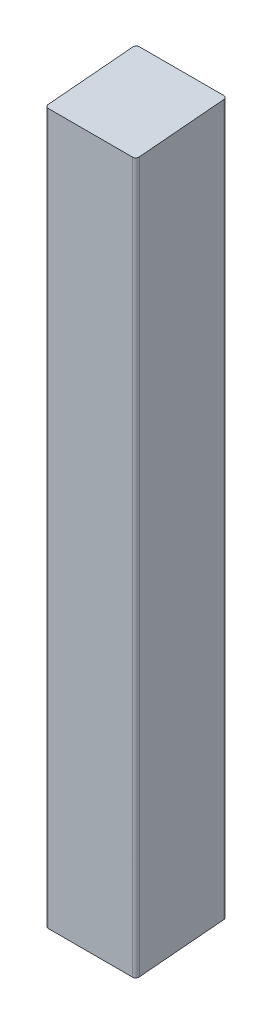
SolidWorks part; units mm, degrees
material "Pine"
ref_plane "Front Plane" through (0, 0, 0) normal (0, 0, 1) x (1, 0, 0)
ref_plane "Top Plane" through (0, 0, 0) normal (0, 1, 0) x (1, 0, 0)
ref_plane "Right Plane" through (0, 0, 0) normal (1, 0, 0) x (0, 0, -1)
sketch "Sketch1" plane through (0, 0, 0) normal (1, 0, 0) x (0, 0, -1)
  line L0 (0, 0) -> (0, 693.7375)
  line L1 (0, 693.7375) -> (88.9, 701.5152)
  line L2 (88.9, 701.5152) -> (88.9, 7.7777)
  line L3 (88.9, 7.7777) -> (0, 0)
  dimension "D1" = 693.7375
  dimension "D2" = 88.9
  dimension "D3" = 85
extrude "Boss-Extrude1" add sketch "Sketch1" along normal mid plane 88.9
fillet "Fillet1" radius 3.175 4 edges at (-44.45, 354.6465, -88.9) (44.45, 354.6465, -88.9) (-44.45, 346.8687, 0) (44.45, 346.8687, 0)
